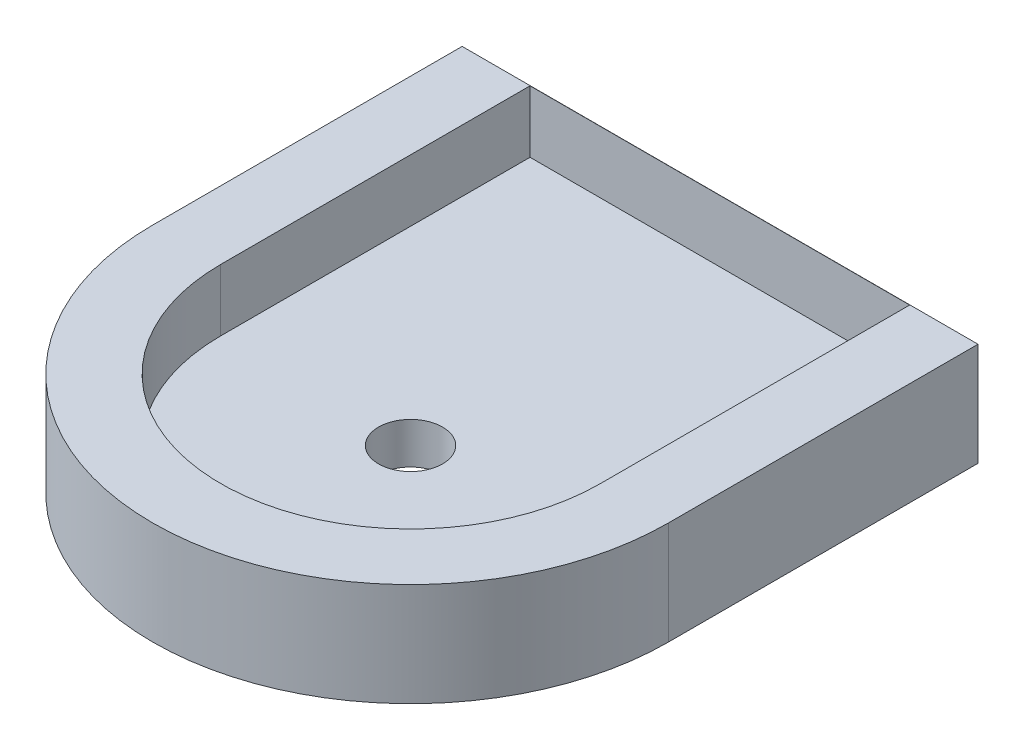
SolidWorks part; units mm, degrees
ref_plane "正面" through (0, 0, 0) normal (0, 0, 1) x (1, 0, 0)
ref_plane "平面" through (0, 0, 0) normal (0, 1, 0) x (1, 0, 0)
ref_plane "右側面" through (0, 0, 0) normal (1, 0, 0) x (0, 0, -1)
sketch "ｽｹｯﾁ1" plane through (0, 0, 0) normal (0, 1, 0) x (1, 0, 0)
  line L0 (0, 0) -> (180, 0) construction
  line L1 (180, 0) -> (180, 60) construction
  line L2 (0, 0) -> (0, -48)
  line L3 (0, -48) -> (25, -48) construction
  line L4 (25, -48) -> (25, -20)
  line L5 (180, 60) -> (0, 0) construction
  line L6 (0, 0) -> (90, 30)
  line L7 (90, 30) -> (90, -20)
  line L8 (90, -20) -> (25, -20)
  line L9 (0, -10) -> (90, -10) construction
  line L10 (90, 19.4591) -> (0, -10.5409) construction
  arc A0 (0, -48) -> (25, -48) centre (12.5, -48) ccw
  circle A1 centre (75.7698, 14.7157) radius 2.55
  circle A2 centre (75, -10) radius 2.55
  circle A3 centre (25, -10) radius 2.55
  circle A4 centre (12.5, -48) radius 7.5
  dimension "D5" = 25
  dimension "D9" = 15
  dimension "D12" = 5.1
  dimension "D13" = 15
  dimension "D1" = 60
  dimension "D2" = 180
  dimension "D3" = 20
  dimension "D4" = 90
  dimension "D6" = 28
  dimension "D7" = 10
  dimension "D8" = 10
  dimension "D10" = 25
  dimension "D11" = 15
extrude "ﾎﾞｽ - 押し出し1" add sketch "ｽｹｯﾁ1" along normal blind 5
fillet "ﾌｨﾚｯﾄ2" radius 5 2 edges at (90, 2.5, -30) (90, 2.5, 20)
sketch "ｽｹｯﾁ2" plane through (0, 5, 0) normal (0, 1, 0) x (1, 0, 0)
  line L0 (3.3, -48) -> (3.3, -33)
  line L1 (3.3, -33) -> (21.7, -33)
  line L2 (21.7, -33) -> (21.7, -48)
  arc A0 (3.3, -48) -> (21.7, -48) centre (12.5, -48) ccw
  point P1 (21.7, -33)
  point P4 (3.3, -33)
  point P6 (3.3, -33.0719)
  point P10 (21.7, -33)
  point P11 (21.7, -33.0425)
  dimension "D1" = 9.2
  dimension "D2" = 15
extrude "ｶｯﾄ - 押し出し1" cut sketch "ｽｹｯﾁ2" against normal through all
sketch "ｽｹｯﾁ4" plane through (0, 5, 0) normal (0, 1, 0) x (1, 0, 0)
  line L0 (0, 0) -> (0, 20)
  line L1 (0, 20) -> (60, 20)
  line L2 (83.4189, 27.8063) -> (0, 0) construction
  line L3 (60, 20) -> (0, 0)
  dimension "D1" = 20
extrude "ﾎﾞｽ - 押し出し2" add sketch "ｽｹｯﾁ4" against normal up to surface (5 mm away) up to face at (12.5, 0, 42.8)
sketch "ｽｹｯﾁ3" plane through (0, 5, 0) normal (0, 1, 0) x (1, 0, 0)
  line L0 (12.5, -60.5) -> (12.5, 5) construction
  line L1 (12.5, 5) -> (20.5, 5) construction
  line L2 (21.7, -33) -> (3.3, -33) construction
  arc A0 (0, -48) -> (25, -48) centre (12.5, -48) ccw construction
  circle A1 centre (20.5, 5) radius 1.55
  circle A2 centre (4.5, 5) radius 1.55
  dimension "D1" = 3.1
  dimension "D2" = 38
  dimension "D3" = 8
extrude "ｶｯﾄ - 押し出し2" cut sketch "ｽｹｯﾁ3" against normal through all
fillet "ﾌｨﾚｯﾄ3" radius 2 2 edges at (60, 2.5, -20) (0, 2.5, -20)
sketch "ｽｹｯﾁ5" plane through (0, 5, 0) normal (0, -1, 0) x (1, 0, 0)
  circle A0 centre (4.5, -5) radius 3
  circle A1 centre (20.5, -5) radius 3
  dimension "D1" = 6
extrude "ｶｯﾄ - 押し出し3" cut sketch "ｽｹｯﾁ5" along normal blind 3
sketch "ｽｹｯﾁ6" plane through (0, 5, 0) normal (0, 1, 0) x (1, 0, 0)
  line L0 (0, 18) -> (0, -48) construction
  line L1 (0, -33) -> (25, -33)
  line L2 (0, -33) -> (0, -62.9204)
  line L3 (0, -62.9204) -> (25, -62.9204)
  line L4 (25, -33) -> (25, -62.9204)
  line L5 (25, -48) -> (25, -20) construction
  line L6 (21.7, -33) -> (3.3, -33) construction
extrude "ｶｯﾄ - 押し出し4" cut sketch "ｽｹｯﾁ6" against normal through all flip side to cut
sketch "ｽｹｯﾁ7" plane through (0, 0, 0) normal (0, -1, 0) x (1, 0, 0)
  line L0 (3.3, 33) -> (3.3, 48) construction
  line L1 (21.7, 48) -> (21.7, 33) construction
  line L2 (3.3, 33) -> (3.3, 48)
  line L3 (21.7, 48) -> (21.7, 33)
  line L4 (3.3, 33) -> (21.7, 33)
  arc A0 (21.7, 48) -> (3.3, 48) centre (12.5, 48) ccw construction
  arc A1 (21.7, 48) -> (3.3, 48) centre (12.5, 48) ccw
  circle A2 centre (12.5, 48) radius 1.55
  dimension "D1" = 3.1
extrude "ﾎﾞｽ - 押し出し3" add sketch "ｽｹｯﾁ7" against normal blind 2
sketch "ｽｹｯﾁ8" plane through (0, 2, 0) normal (0, 1, 0) x (1, 0, 0)
  line L0 (21.7, -48) -> (21.7, -33) construction
  line L1 (3.3, -33) -> (21.7, -33)
  line L2 (3.3, -33) -> (3.3, -33.01)
  line L3 (3.3, -33.01) -> (21.7, -33.01)
  line L4 (21.7, -33) -> (21.7, -33.01)
  dimension "D1" = 0.01
extrude "ﾎﾞｽ - 押し出し4" add sketch "ｽｹｯﾁ8" along normal up to surface (3 mm away) up to face at (12.5, 5, 43.2125)
